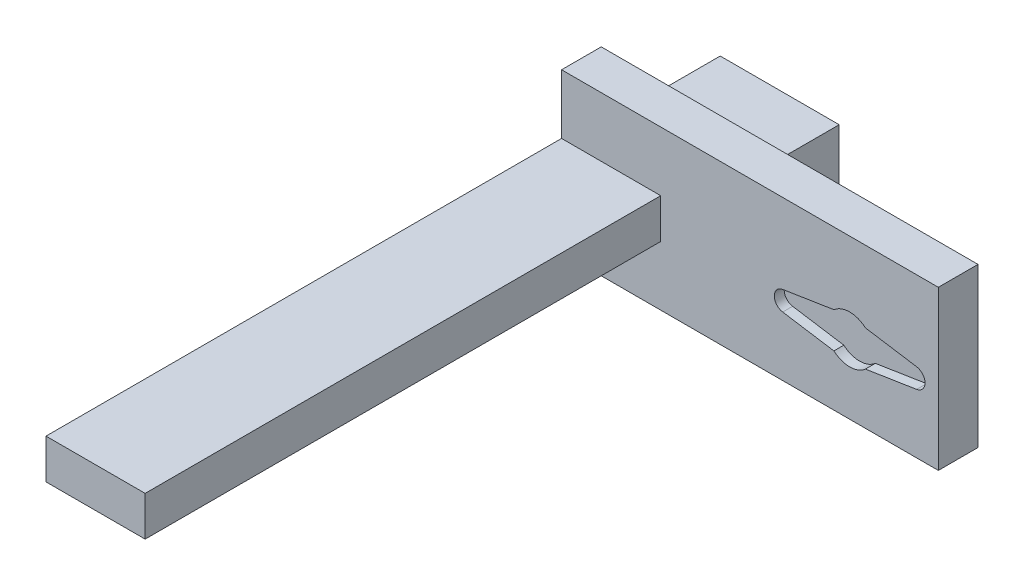
SolidWorks part; units mm, degrees
ref_plane "Front Plane" through (0, 0, 0) normal (0, 0, 1) x (1, 0, 0)
ref_plane "Top Plane" through (0, 0, 0) normal (0, 1, 0) x (1, 0, 0)
ref_plane "Right Plane" through (0, 0, 0) normal (1, 0, 0) x (0, 0, -1)
sketch "Sketch3" plane through (0, 0, 0) normal (0, 0, 1) x (1, 0, 0)
  line L1 (-22.6388, -7.4411) -> (22.3612, -7.4411)
  line L2 (-22.6388, -7.4411) -> (-22.6388, 7.5589)
  line L3 (-22.6388, 7.5589) -> (22.3612, 7.5589)
  line L4 (22.3612, -7.4411) -> (22.3612, 7.5589)
  dimension "D1" = 15
  dimension "D2" = 45
extrude "Boss-Extrude1" add sketch "Sketch3" against normal blind 10
sketch "Sketch2" plane through (0, 0, 0) normal (0, 0, 1) x (1, 0, 0)
  line L0 (-16.8881, 2.4697) -> (-3.9686, 4.5)
  line L1 (-16.8881, -2.4697) -> (-3.9686, -4.5)
  line L2 (3.9686, 4.5) -> (16.8881, 2.4697)
  line L3 (16.8881, -2.4697) -> (3.9686, -4.5)
  arc A0 (-16.8881, 2.4697) -> (-16.8881, -2.4697) centre (-16.5, 0) ccw
  arc A1 (-3.9686, 4.5) -> (3.9686, 4.5) centre (0, 0) cw
  arc A2 (-3.9686, -4.5) -> (3.9686, -4.5) centre (0, 0) ccw
  arc A3 (16.8881, -2.4697) -> (16.8881, 2.4697) centre (16.5, 0) ccw
extrude "Cut-Extrude1" cut sketch "Sketch2" against normal blind 2.5
sketch "Sketch11" plane through (0, -7.4411, 0) normal (0, -1, 0) x (1, 0, 0)
  line L0 (8.25, 0) -> (-8.25, 0) construction
  line L1 (22.3612, -10) -> (-22.6388, -10)
  line L2 (22.3612, -10) -> (22.3612, 0)
  line L3 (22.3612, 0) -> (-22.6388, 0)
  line L4 (-22.6388, -10) -> (-22.6388, 0)
  line L5 (-22.6388, -10) -> (-22.6388, 0) construction
extrude "Boss-Extrude5" add sketch "Sketch11" along normal blind 10
sketch "Sketch14" plane through (0, 7.5589, 0) normal (0, 1, 0) x (1, 0, 0)
  line L0 (-8.25, 0) -> (8.25, 0) construction
  line L1 (22.3612, 10) -> (-22.6388, 10)
  line L2 (22.3612, 10) -> (22.3612, 0)
  line L3 (22.3612, 0) -> (-22.6388, 0)
  line L4 (-22.6388, 10) -> (-22.6388, 0)
  line L5 (-22.6388, 10) -> (-22.6388, 0) construction
extrude "Boss-Extrude7" add sketch "Sketch14" along normal blind 15
sketch "Sketch20" plane through (-22.6388, 0, 0) normal (-1, 0, 0) x (0, 0, 1)
  line L0 (0, -22) -> (0, 22) construction
  line L1 (-10, 22.5589) -> (0, 22.5589)
  line L2 (-10, 22.5589) -> (-10, -17.4411)
  line L3 (-10, -17.4411) -> (0, -17.4411)
  line L4 (0, 22.5589) -> (0, -17.4411)
  line L5 (0, -17.4411) -> (-10, -17.4411) construction
extrude "Boss-Extrude10" add sketch "Sketch20" along normal blind 50
sketch "Sketch21" plane through (0, 0, 0) normal (0, 0, 1) x (1, 0, 0)
  line L0 (-72.6388, -17.4411) -> (-72.6388, 22.5589) construction
  line L1 (-72.6388, 7.5589) -> (-47.6388, 7.5589)
  line L2 (-72.6388, 7.5589) -> (-72.6388, -2.4411)
  line L3 (-72.6388, -2.4411) -> (-47.6388, -2.4411)
  line L4 (-47.6388, 7.5589) -> (-47.6388, -2.4411)
  line L5 (-72.6388, 22.5589) -> (22.3612, 22.5589) construction
  dimension "D1" = 25
  dimension "D2" = 10
  dimension "D3" = 15
extrude "Boss-Extrude11" add sketch "Sketch21" along normal blind 130
sketch "Sketch22" plane through (0, 0, -10) normal (0, 0, -1) x (-1, 0, 0)
  line L0 (72.6388, 22.5589) -> (72.6388, -17.4411) construction
  line L1 (42.6388, 5.5589) -> (72.6388, 5.5589)
  line L2 (42.6388, 5.5589) -> (42.6388, -0.4411)
  line L3 (42.6388, -0.4411) -> (72.6388, -0.4411)
  line L4 (72.6388, 5.5589) -> (72.6388, -0.4411)
  line L5 (42.6388, 5.5589) -> (72.6388, -0.4411) construction
  line L6 (42.6388, -0.4411) -> (72.6388, 5.5589) construction
  line L7 (72.6388, -17.4411) -> (-22.3612, -17.4411) construction
  point P0 (57.6388, 2.5589)
  dimension "D1" = 20
  dimension "D2" = 30
  dimension "D3" = 6
extrude "Boss-Extrude12" add sketch "Sketch22" along normal blind 30
sketch "Sketch23" plane through (0, -0.4411, 0) normal (0, -1, 0) x (1, 0, 0)
  line L1 (-72.6388, -10) -> (-42.6388, -10)
  line L2 (-72.6388, -10) -> (-72.6388, -40)
  line L3 (-72.6388, -40) -> (-42.6388, -40)
  line L4 (-42.6388, -10) -> (-42.6388, -40)
extrude "Boss-Extrude13" add sketch "Sketch23" along normal blind 8.5
